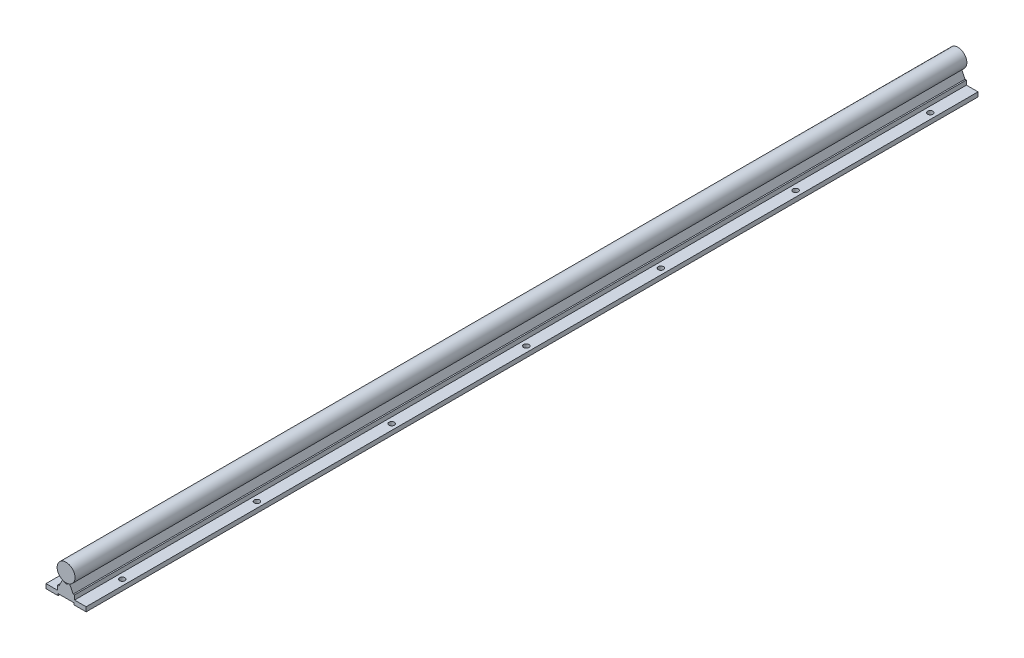
SolidWorks part; units mm, degrees
material "1060 Alloy"
ref_plane "Front Plane" through (0, 0, 0) normal (0, 0, 1) x (1, 0, 0)
ref_plane "Top Plane" through (0, 0, 0) normal (0, 1, 0) x (1, 0, 0)
ref_plane "Right Plane" through (0, 0, 0) normal (1, 0, 0) x (0, 0, -1)
sketch "Sketch1" plane through (0, 0, 0) normal (0, 0, 1) x (1, 0, 0)
  line L0 (0, 0) -> (0, -27) construction
  line L1 (-22.5, -27) -> (-9, -27)
  line L2 (-22.5, -27) -> (-22.5, -22)
  line L3 (-22.5, -22) -> (-9.5, -22)
  line L4 (22.5, -22) -> (22.5, -27)
  line L5 (-9, -27) -> (-9, -25)
  line L6 (-9, -25) -> (9, -25)
  line L7 (9, -25) -> (9, -27)
  line L8 (9, -27) -> (22.5, -27)
  line L9 (-9.5, -22) -> (-9.5, -17)
  line L10 (-9.5, -17) -> (-8, -17)
  line L11 (9.5, -17) -> (9.5, -22)
  line L12 (8, -17) -> (4, -9.1652)
  line L13 (-4, -9.1652) -> (-8, -17)
  line L14 (-4, -9.1652) -> (0, -11)
  line L15 (0, -11) -> (4, -9.1652)
  line L16 (8, -17) -> (9.5, -17)
  line L17 (9.5, -22) -> (22.5, -22)
  circle A0 centre (0, 0) radius 10
  dimension "D1" = 20
  dimension "D3" = 27
  dimension "D2" = 45
  dimension "D4" = 5
  dimension "D5" = 2
  dimension "D6" = 18
  dimension "D7" = 19
  dimension "D8" = 5
  dimension "D9" = 16
  dimension "D10" = 4
  dimension "D11" = 11
  dimension "D12" = 1.5
  dimension "D13" = 4
extrude "Boss-Extrude1" add sketch "Sketch1" against normal blind 1000
sketch "Sketch2" plane through (0, -22, 0) normal (0, 1, 0) x (1, 0, 0)
  line L0 (16, 1000) -> (16, 0) construction
  line L1 (9.5, 1000) -> (22.5, 1000) construction
  line L2 (9.5, 0) -> (22.5, 0) construction
  circle A0 centre (16, 47) radius 3
  circle A1 centre (16, 198) radius 3
  circle A2 centre (16, 349) radius 3
  circle A3 centre (16, 500) radius 3
  circle A4 centre (16, 651) radius 3
  circle A5 centre (16, 802) radius 3
  circle A6 centre (16, 953) radius 3
  dimension "D1" = 6
  dimension "D2" = 47
  dimension "D3" = 151
  dimension "D4" = 6
  dimension "D5" = 6
extrude "Cut-Extrude1" cut sketch "Sketch2" against normal blind 1000
mirror "Mirror1" about plane through (0, 0, 0) normal (1, 0, 0) of "Cut-Extrude1"
